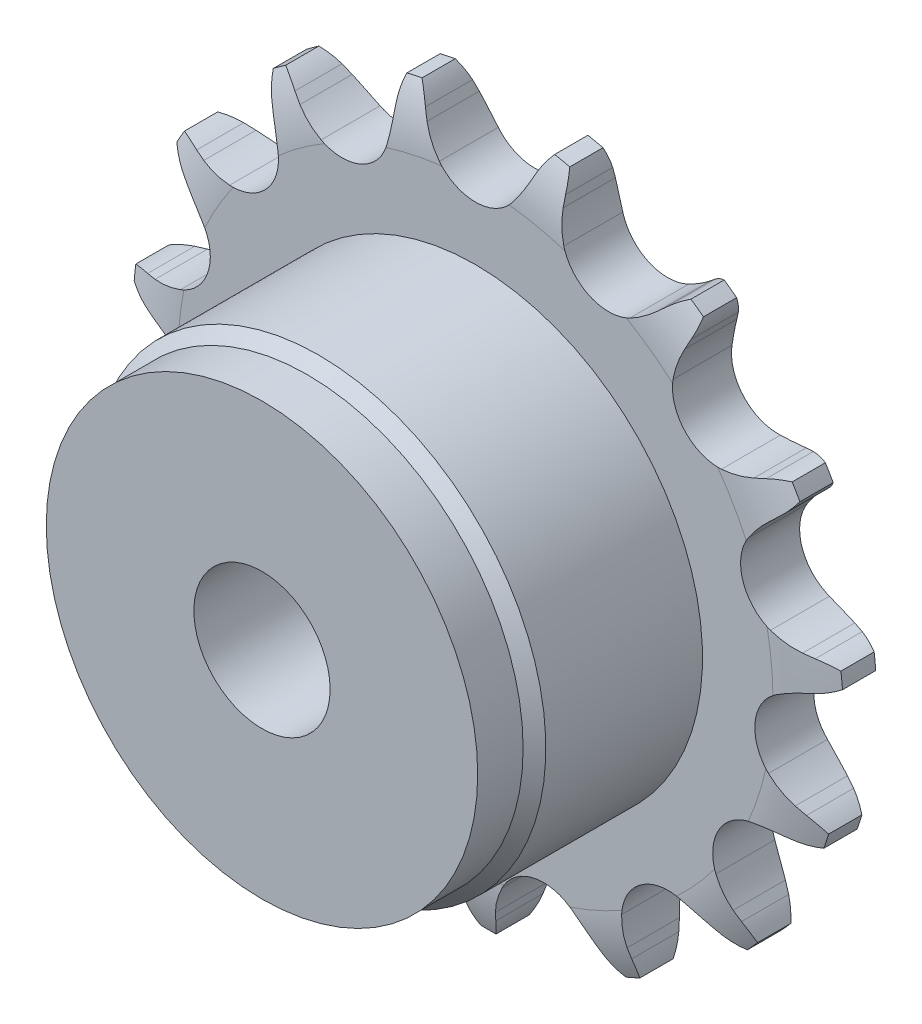
SolidWorks part; units mm, degrees
ref_plane "Front Plane" through (0, 0, 0) normal (0, 0, 1) x (1, 0, 0)
ref_plane "Top Plane" through (0, 0, 0) normal (0, 1, 0) x (1, 0, 0)
ref_plane "Right Plane" through (0, 0, 0) normal (1, 0, 0) x (0, 0, -1)
sketch "Sketch0" plane through (0, 0, 0) normal (0, 0, 1) x (1, 0, 0)
  line L0 (3, -14.1139) -> (0, 0) construction
  line L1 (0, 0) -> (8.4813, -11.6735) construction
  line L2 (0, 0) -> (-3, -14.1139) construction
  line L3 (3, -14.1139) -> (8.4813, -11.6735) construction
  line L4 (3, -14.1139) -> (-3, -14.1139) construction
  line L5 (5.4587, -13.8191) -> (5.1921, -13.4619)
  line L6 (3, -14.1139) -> (0, -14.7516) construction
  line L7 (0.6339, -14.8447) -> (0.7322, -14.4099)
  line L8 (0, -14.1139) -> (0, -15.9139) construction
  line L9 (4.2889, -12.5222) -> (0.9862, -16.6008) construction
  line L10 (0, 0) -> (0, -14.1139) construction
  line L11 (5.1921, -13.4619) -> (0.9862, -16.6008) construction
  line L12 (0, -15.9139) -> (0, -16.1712) construction
  line L13 (8.1159, -11.8362) -> (5.4587, -13.8191) construction
  circle A0 centre (0, 0) radius 15.9139 construction
  circle A1 centre (0, 0) radius 14.4292 construction
  arc A2 (-3.2007, -17.3745) -> (9.9908, -14.5706) centre (0, 0) ccw
  circle A3 centre (0, 0) radius 16.1712 construction
  circle A4 centre (3, -14.1139) radius 2 construction
  arc A7 (4.2889, -12.5222) -> (1.1751, -13.1841) centre (3, -14.1139) ccw
  circle A8 centre (3, -14.1139) radius 2.0481 construction
  arc A9 (5.4587, -13.8191) -> (9.9908, -14.5706) centre (8.1159, -11.8362) ccw
  arc A10 (5.1921, -13.4619) -> (4.2889, -12.5222) centre (0.9862, -16.6008) ccw
  arc A11 (0.6339, -14.8447) -> (-3.2007, -17.3745) centre (-2.6, -14.1139) cw
  arc A12 (0.7322, -14.4099) -> (1.1751, -13.1841) centre (5.8512, -15.5667) cw
  dimension "D1" = 2.0481
  dimension "R" = 2.0481
sketch "Sketch1" plane through (0, 0, 0) normal (1, 0, 0) x (0, 0, -1)
  line L0 (1.3, 0) -> (-1.3, 0)
  line L1 (-1.3, 0) -> (-1.3, 13.1014)
  line L2 (-1.3, 14.4292) -> (0, 14.4292) construction
  line L3 (-0.6, 15.9139) -> (0.6, 15.9139)
  line L5 (1.3, 13.1014) -> (1.3, 0)
  line L7 (0, 15.9139) -> (0, 0) construction
  line L8 (-1.3, 13.1014) -> (1.3, 13.1014) construction
  line L9 (0, 15.9139) -> (0, -15.9139) construction
  line L10 (-1.3, 13.1014) -> (-1.3, 15.9139) construction
  line L11 (-1.3, 15.9139) -> (-0.6, 15.9139) construction
  line L12 (0.6, 15.9139) -> (1.3, 15.9139) construction
  line L13 (1.3, 15.9139) -> (1.3, 13.1014) construction
  line L14 (0, 0) -> (-6.4008, 0) construction
  line L15 (-1.3, 14.4292) -> (-1.3, 10.3292) construction
  line L22 (1.3, 0) -> (-8.7, 0) construction
  line L24 (-1.3, 0) -> (-1.3, 10.3292) construction
  arc A0 (-0.6, 15.9139) -> (-1.3, 13.1014) centre (4.7, 13.1014) ccw
  arc A1 (0.6, 15.9139) -> (1.3, 13.1014) centre (-4.7, 13.1014) cw
  dimension "R" = 6
revolve "Revolve1" add sketch "Sketch1" angle 360 mid plane about L0
extrude "Cut-Extrude1" cut sketch "Sketch0" against normal through all and the other way through all
pattern_circular "CirPattern1" count 15 over 360 about axis through (0, 0, 0) along (0, 0, 1) of "Cut-Extrude1"
sketch "Sketch2" plane through (0, 0, 0) normal (0, 0, 1) x (1, 0, 0)
  circle A0 centre (0, 0) radius 3 construction
  circle A1 centre (0, 0) radius 10
  circle A2 centre (0, 0) radius 15.65 construction
  dimension "Bore" = 6
  dimension "Hub Dia." = 20
  dimension "OD" = 31.3
extrude "Boss-Extrude1" add sketch "Sketch2" along normal up to vertex (8.7 mm away) from surface at 1.3 starting at face at (0, 0, 1.3)
sketch "Sketch3" plane through (0, 0, 0) normal (0, 0, 1) x (1, 0, 0)
  circle A0 centre (0, 0) radius 3 construction
  circle A1 centre (0, 0) radius 3
extrude "Cut-Extrude2" cut sketch "Sketch3" along normal through all and the other way through all
sketch "Sketch4" plane through (0, 0, 0) normal (1, 0, 0) x (0, 0, -1)
  line L0 (-8.7, 10) -> (-8.7, 9.5)
  line L1 (-1.3, 15.9139) -> (-3.25, 15.9139)
  line L2 (-1.3, 15.9139) -> (-1.3, 10.3292)
  line L3 (-1.3, 10.3292) -> (-3.25, 10.3292)
  line L4 (-3.25, 15.9139) -> (-3.25, 10.3292)
  line L9 (-8.7, 9.5) -> (-8.2, 10)
  line L10 (-8.2, 10) -> (-8.7, 10)
  dimension "C" = 0.5
  dimension "D3" = 1.95
revolve "Cut-Revolve1" cut sketch "Sketch4" angle 360 mid plane about L22
sketch "Sketch5" plane through (0, 0, 0) normal (0, 0, 1) x (1, 0, 0)
  circle A0 centre (0, 0) radius 15.65 construction
  circle A1 centre (0, 0) radius 15.65
extrude "Cut-Extrude3" cut sketch "Sketch5" against normal through all and the other way through all flip side to cut
sketch "Sketch6" plane through (0, 0, 8.7) normal (0, 0, 1) x (1, 0, 0)
  circle A0 centre (0, 0) radius 9.5
  circle A1 centre (0, 0) radius 3
extrude "Boss-Extrude2" add sketch "Sketch6" along normal blind 2
equation "\"360/N@Sketch0\" = 360/\"Teeth@CirPattern1\""
equation "\"Ds@Sketch0\" = 1.005 * \"Dr@Sketch0\" + ( 0.003 * 25.4 ) "
equation "\"R@Sketch0\" = 1/2 * \"Ds@Sketch0\""
equation "\"A@Sketch0\" = 35 +  ( 60 / \"Teeth@CirPattern1\" ) "
equation "\"B@Sketch0\" = 18 -  ( 56 / \"Teeth@CirPattern1\" )"
equation "\"ac@Sketch0\" = 0.8 * \"Dr@Sketch0\""
equation "\"ab@Sketch0\" = 1.4 * \"Dr@Sketch0\""
equation "\"J@Sketch0\" = 0.3 * \"Pitch@Sketch0\""
equation "\"D3@Sketch4\" = \"t@Sketch1\" * 3 / 4"
